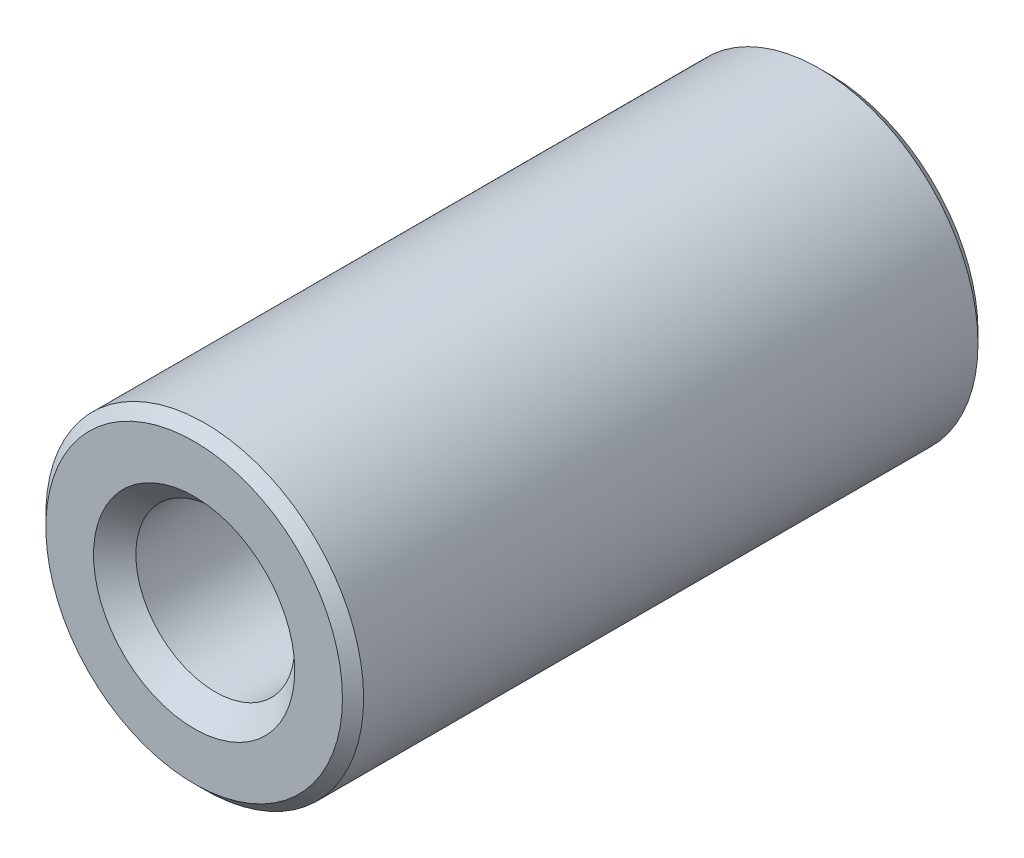
SolidWorks part; units mm, degrees
ref_plane "前视基准面" through (0, 0, 0) normal (0, 0, 1) x (1, 0, 0)
ref_plane "上视基准面" through (0, 0, 0) normal (0, 1, 0) x (1, 0, 0)
ref_plane "右视基准面" through (0, 0, 0) normal (1, 0, 0) x (0, 0, -1)
sketch "草图1" plane through (0, 0, 0) normal (0, 1, 0) x (1, 0, 0)
  line L0 (1.5, -17.3999) -> (0, -17.3999)
  line L1 (0, -17.3999) -> (0, -20.6001)
  line L2 (0, -20.6001) -> (1.5, -20.6001)
  line L3 (1.5, -20.6001) -> (1.5, -24.6001)
  line L4 (1.5, -24.6001) -> (1.8999, -25)
  line L5 (1.8999, -25) -> (2.7999, -25)
  line L6 (2.7999, -25) -> (3, -24.7999)
  line L7 (3, -24.7999) -> (3, -13.2)
  line L8 (3, -13.2) -> (2.8, -13)
  line L9 (2.8, -13) -> (1.8999, -13)
  line L10 (1.8999, -13) -> (1.5, -13.3999)
  line L11 (1.5, -13.3999) -> (1.5, -17.3999)
  line L12 (0, 25.0031) -> (0, -25) construction
  dimension "D1" = 12
  dimension "D2" = 0.9
  dimension "D3" = 135
  dimension "D4" = 45.001
  dimension "D5" = 4
  dimension "D6" = 4
  dimension "D7" = 1.5
  dimension "D8" = 0.9
  dimension "D9" = 135.001
  dimension "D10" = 135.001
  dimension "D11" = 1.5
  dimension "D12" = 0.3999
  dimension "D13" = 0.3999
revolve "旋转1" add sketch "草图1" angle 360 about L12
